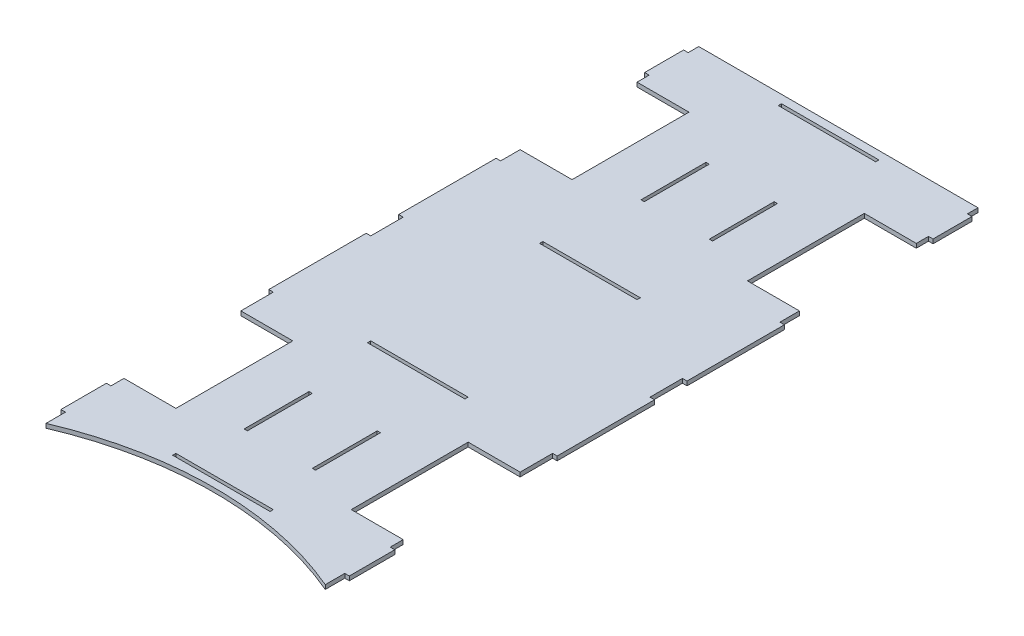
SolidWorks part; units mm, degrees
ref_plane "Front Plane" through (0, 0, 0) normal (0, 0, 1) x (1, 0, 0)
ref_plane "Top Plane" through (0, 0, 0) normal (0, 1, 0) x (1, 0, 0)
ref_plane "Right Plane" through (0, 0, 0) normal (1, 0, 0) x (0, 0, -1)
sketch "Sketch1" plane through (0, 0, 0) normal (0, 1, 0) x (1, 0, 0)
  line L0 (-69.9397, 82) -> (66.2635, 82) construction
  line L1 (-43, 100) -> (43, 100)
  line L2 (-43, 100) -> (-43, -100)
  line L3 (-43, -100) -> (43, -100) construction
  line L4 (43, 100) -> (43, -100)
  line L5 (-43, 100) -> (43, -100) construction
  line L6 (-43, -100) -> (43, 100) construction
  line L7 (-43, 82) -> (-27, 82)
  line L8 (-43, 82) -> (-43, 46)
  line L9 (-43, 46) -> (-27, 46)
  line L10 (-27, 82) -> (-27, 46)
  line L11 (43, 82) -> (27, 82)
  line L12 (43, 82) -> (43, 46)
  line L13 (43, 46) -> (27, 46)
  line L14 (27, 82) -> (27, 46)
  line L16 (-109.9475, 3) -> (122.7452, 3) construction
  line L17 (43, -40) -> (27, -40)
  line L18 (27, -76) -> (27, -40)
  line L19 (43, -76) -> (27, -76)
  line L20 (43, -76) -> (43, -40)
  line L21 (-43, -40) -> (-27, -40)
  line L22 (-27, -76) -> (-27, -40)
  line L23 (-43, -76) -> (-27, -76)
  line L24 (-43, -76) -> (-43, -40)
  arc A0 (-43, -100) -> (43, -100) centre (0, -201.1686) cw
  point P0 (0, 0)
  dimension "D1" = 200
  dimension "D2" = 86
  dimension "D3" = 36
  dimension "D4" = 18
  dimension "D5" = 16
  dimension "D6" = 43
extrude "Boss-Extrude1" add sketch "Sketch1" along normal blind 1.3 contours L2 A0 L4 L13 L14 L11 L1 L7 L10 L9
sketch "Sketch2" plane through (0, 0, 0) normal (0, 1, 0) x (1, 0, 0)
  line L0 (43, 100) -> (43, 82) construction
  line L1 (43, 97.75) -> (44.4, 97.75)
  line L2 (43, 97.75) -> (43, 85.75)
  line L3 (43, 85.75) -> (44.4, 85.75)
  line L4 (44.4, 97.75) -> (44.4, 85.75)
  line L5 (-43, 100) -> (43, 100) construction
  line L6 (43, 46) -> (43, -40) construction
  line L7 (43, 40) -> (44.4, 40)
  line L8 (43, 40) -> (43, 10)
  line L9 (43, 10) -> (44.4, 10)
  line L10 (44.4, 40) -> (44.4, 10)
  line L11 (43, -76) -> (43, -100) construction
  line L12 (43, -80) -> (44.4, -80)
  line L13 (43, -80) -> (43, -94)
  line L14 (43, -94) -> (44.4, -94)
  line L15 (44.4, -80) -> (44.4, -94)
  line L17 (43, 0) -> (44.4, 0)
  line L18 (43, 0) -> (43, -30)
  line L19 (43, -30) -> (44.4, -30)
  line L20 (44.4, 0) -> (44.4, -30)
  dimension "D1" = 1.4
  dimension "D2" = 2.25
  dimension "D3" = 12
  dimension "D4" = 60
  dimension "D5" = 1.4
  dimension "D6" = 30
  dimension "D7" = 1.4
  dimension "D8" = 180
  dimension "D9" = 14
  dimension "D10" = 30
  dimension "D11" = 10
  dimension "D12" = 1.4
extrude "Boss-Extrude2" add sketch "Sketch2" along normal blind 1.3
mirror "Mirror1" about plane through (0, 0, 0) normal (1, 0, 0) of "Boss-Extrude2"
sketch "Sketch3" plane through (0, 1.3, 0) normal (0, 1, 0) x (1, 0, 0)
  line L0 (0, -55) -> (0, 55) construction
  line L1 (-15, 98.5) -> (15, 98.5)
  line L2 (-15, 98.5) -> (-15, 97.5)
  line L3 (-15, 97.5) -> (15, 97.5)
  line L4 (15, 98.5) -> (15, 97.5)
  line L5 (-15, 98.5) -> (15, 97.5) construction
  line L6 (-15, 97.5) -> (15, 98.5) construction
  line L7 (-43, 100) -> (43, 100) construction
  point P0 (0, 98)
  dimension "D1" = 1
  dimension "D2" = 1.5
  dimension "D3" = 30
extrude "Cut-Extrude1" cut sketch "Sketch3" against normal through all
sketch "Sketch4" plane through (0, 1.3, 0) normal (0, 1, 0) x (1, 0, 0)
  line L0 (0, -55) -> (0, 55) construction
  line L1 (-15, -88) -> (15, -88)
  line L2 (-15, -88) -> (-15, -89)
  line L3 (-15, -89) -> (15, -89)
  line L4 (15, -88) -> (15, -89)
  line L5 (-15, -88) -> (15, -89) construction
  line L6 (-15, -89) -> (15, -88) construction
  line L7 (-43, 100) -> (43, 100) construction
  point P0 (0, -88.5)
  dimension "D1" = 1
  dimension "D2" = 30
  dimension "D3" = 188
extrude "Cut-Extrude2" cut sketch "Sketch4" against normal through all
sketch "Sketch6" plane through (0, 1.3, 0) normal (0, 1, 0) x (1, 0, 0)
  line L0 (0, -55) -> (0, 55) construction
  line L1 (-15, 25) -> (15, 25)
  line L2 (-15, 25) -> (-15, 24)
  line L3 (-15, 24) -> (15, 24)
  line L4 (15, 25) -> (15, 24)
  line L5 (-15, 25) -> (15, 24) construction
  line L6 (-15, 24) -> (15, 25) construction
  line L8 (-43, 100) -> (43, 100) construction
  point P0 (0, 24.5)
  dimension "D1" = 30
  dimension "D2" = 1
  dimension "D3" = 75
extrude "Cut-Extrude3" cut sketch "Sketch6" against normal through all
sketch "Sketch7" plane through (0, 1.3, 0) normal (0, 1, 0) x (1, 0, 0)
  line L0 (0, -55) -> (0, 55) construction
  line L1 (-11, -51) -> (-10, -51)
  line L2 (-11, -51) -> (-11, -71)
  line L3 (-11, -71) -> (-10, -71)
  line L4 (-10, -51) -> (-10, -71)
  line L5 (10, -51) -> (11, -51)
  line L6 (10, -51) -> (10, -71)
  line L7 (10, -71) -> (11, -71)
  line L8 (11, -51) -> (11, -71)
  line L9 (-15, -28) -> (15, -28)
  line L10 (-15, -28) -> (-15, -29)
  line L11 (-15, -29) -> (15, -29)
  line L12 (15, -28) -> (15, -29)
  line L13 (-15, -28) -> (15, -29) construction
  line L14 (-15, -29) -> (15, -28) construction
  line L15 (-43, 100) -> (43, 100) construction
  point P8 (0, -28.5)
  dimension "D1" = 1
  dimension "D2" = 1
  dimension "D3" = 1
  dimension "D4" = 30
  dimension "D5" = 20
  dimension "D6" = 20
  dimension "D7" = 10
  dimension "D8" = 10
  dimension "D9" = 22
  dimension "D10" = 128
  dimension "D11" = 22
extrude "Cut-Extrude4" cut sketch "Sketch7" against normal through all
sketch "Sketch8" plane through (0, 1.3, 0) normal (0, 1, 0) x (1, 0, 0)
  line L0 (-15, 97.5) -> (39.4073, 97.5) construction
  line L1 (-15, 97.5) -> (15, 97.5) construction
  line L2 (-15, 25) -> (39.4073, 25) construction
  line L3 (39.4073, 25) -> (39.4073, 97.5) construction
  line L4 (-59.8934, 61.25) -> (77.8429, 61.25) construction
  line L5 (-11, 71.25) -> (-10, 71.25)
  line L6 (-11, 71.25) -> (-11, 51.25)
  line L7 (-11, 51.25) -> (-10, 51.25)
  line L8 (-10, 71.25) -> (-10, 51.25)
  line L9 (-11, 71.25) -> (-10, 51.25) construction
  line L10 (-11, 51.25) -> (-10, 71.25) construction
  line L11 (10, 71.25) -> (11, 71.25)
  line L12 (10, 71.25) -> (10, 51.25)
  line L13 (10, 51.25) -> (11, 51.25)
  line L14 (11, 71.25) -> (11, 51.25)
  line L15 (10, 71.25) -> (11, 51.25) construction
  line L16 (10, 51.25) -> (11, 71.25) construction
  line L17 (0, -55) -> (0, 55) construction
  point P7 (10.5, 61.25)
  point P8 (-10.5, 61.25)
  dimension "D1" = 36.25
  dimension "D2" = 1
  dimension "D3" = 1
  dimension "D4" = 20
  dimension "D5" = 20
  dimension "D6" = 10
  dimension "D7" = 10
extrude "Cut-Extrude5" cut sketch "Sketch8" against normal through all
sketch "Sketch9" plane through (0, 0, 0) normal (0, 1, 0) x (1, 0, 0)
  line L1 (-43, 100) -> (43, 100)
  line L2 (-43, 100) -> (-43, 101)
  line L3 (-43, 101) -> (43, 101)
  line L4 (43, 100) -> (43, 101)
  dimension "D1" = 1
extrude "Boss-Extrude3" add sketch "Sketch9" along normal blind 1.3
